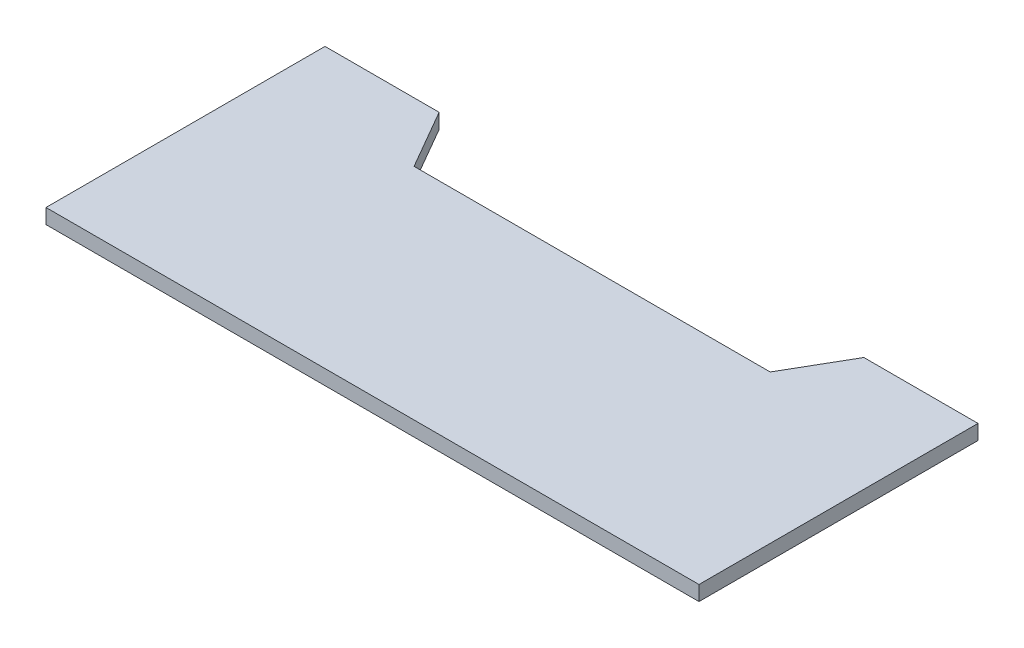
SolidWorks part; units mm, degrees
ref_plane "Front Plane" through (0, 0, 0) normal (0, 0, 1) x (1, 0, 0)
ref_plane "Top Plane" through (0, 0, 0) normal (0, 1, 0) x (1, 0, 0)
ref_plane "Right Plane" through (0, 0, 0) normal (1, 0, 0) x (0, 0, -1)
sketch "Sketch1" plane through (0, 0, 0) normal (0, 1, 0) x (1, 0, 0)
  line L1 (0, 0) -> (279.4, 0)
  line L2 (0, 0) -> (0, 119.38)
  line L3 (0, 119.38) -> (279.4, 119.38)
  line L4 (279.4, 0) -> (279.4, 119.38)
  dimension "D1" = 279.4
  dimension "D2" = 119.38
extrude "Boss-Extrude1" add sketch "Sketch1" along normal blind 6.35
sketch "Sketch2" plane through (0, 6.35, 0) normal (0, 1, 0) x (1, 0, 0)
  line L0 (48.8353, 119.38) -> (63.5, 93.98)
  line L1 (279.4, 119.38) -> (0, 119.38) construction
  line L2 (63.5, 93.98) -> (215.9, 93.98)
  line L3 (215.9, 93.98) -> (230.5647, 119.38)
  line L4 (48.8353, 119.38) -> (230.5647, 119.38)
  point P4 (139.7, 93.98)
  point P7 (139.7, 119.38)
  dimension "D1" = 120
  dimension "D2" = 25.4
  dimension "D3" = 152.4
extrude "Cut-Extrude1" cut sketch "Sketch2" against normal through all
